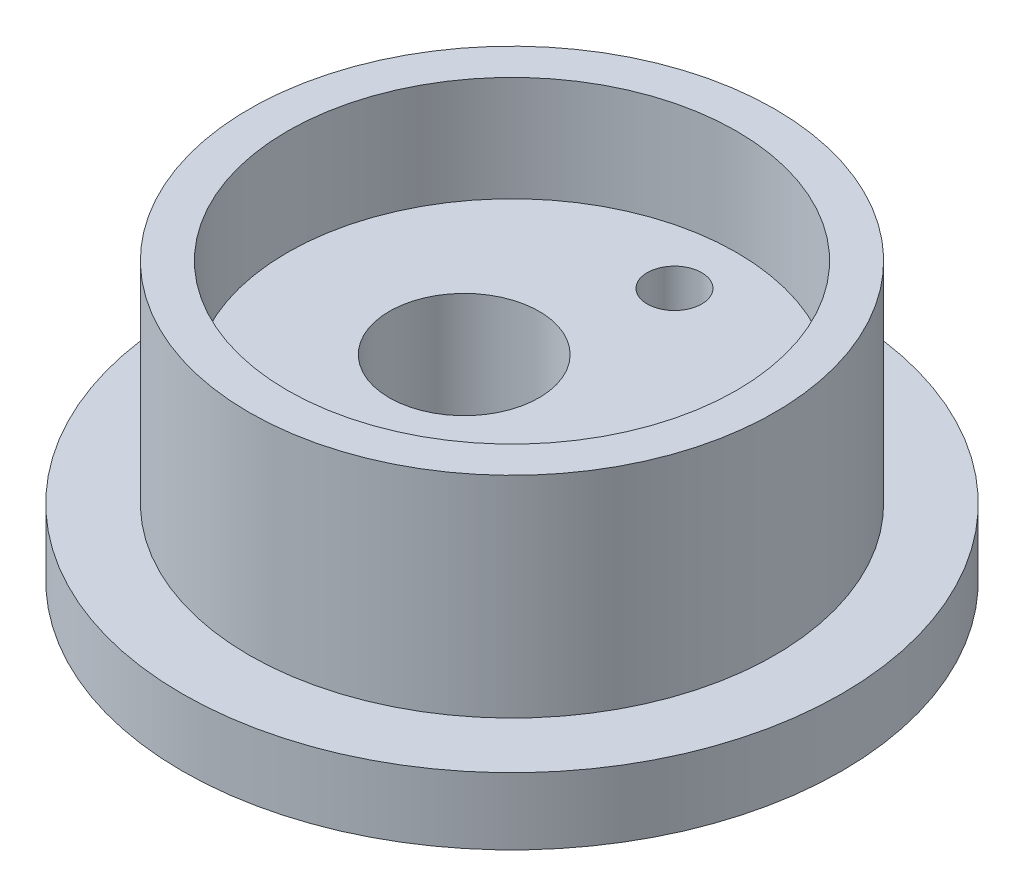
SolidWorks part; units mm, degrees
ref_plane "Front Plane" through (0, 0, 0) normal (0, 0, 1) x (1, 0, 0)
ref_plane "Top Plane" through (0, 0, 0) normal (0, 1, 0) x (1, 0, 0)
ref_plane "Right Plane" through (0, 0, 0) normal (1, 0, 0) x (0, 0, -1)
sketch "Sketch1" plane through (0, 0, 0) normal (0, 0, 1) x (1, 0, 0)
  line L6 (0, 0) -> (876.3, 0)
  line L7 (876.3, 0) -> (876.3, 177.8)
  line L8 (876.3, 177.8) -> (698.5, 177.8)
  line L9 (698.5, 177.8) -> (698.5, 736.6)
  line L10 (698.5, 736.6) -> (596.9, 736.6)
  line L11 (0, -147.1833) -> (0, 945.534) construction
  line L12 (0, 457.2) -> (0, 0)
  line L13 (596.9, 736.6) -> (596.9, 457.2)
  line L14 (596.9, 457.2) -> (0, 457.2)
  dimension "D1" = 177.8
  dimension "D2" = 736.6
  dimension "D3" = 279.4
  dimension "D4" = 876.3
  dimension "D5" = 698.5
  dimension "D6" = 596.9
revolve "Revolve1" add sketch "Sketch1" angle 360 about L11
sketch "Sketch2" plane through (0, 457.2, 0) normal (0, 1, 0) x (1, 0, 0)
  line L0 (0, -1029.4631) -> (0, 1095.9755) construction
  line L1 (991.7728, 0) -> (-1030.2022, 0) construction
  circle A0 centre (-127, 0) radius 199.136
  circle A1 centre (0, 431.8) radius 72.39
  circle A2 centre (431.8, 0) radius 72.39
  circle A3 centre (0, -431.8) radius 72.39
  dimension "D3" = 398.272
  dimension "D4" = 144.78
  dimension "D5" = 144.78
  dimension "D6" = 144.78
  dimension "D1" = 127
  dimension "D2" = 0
  dimension "D7" = 431.8
  dimension "D8" = 431.8
  dimension "D9" = 431.8
extrude "Cut-Extrude1" cut sketch "Sketch2" against normal through all
